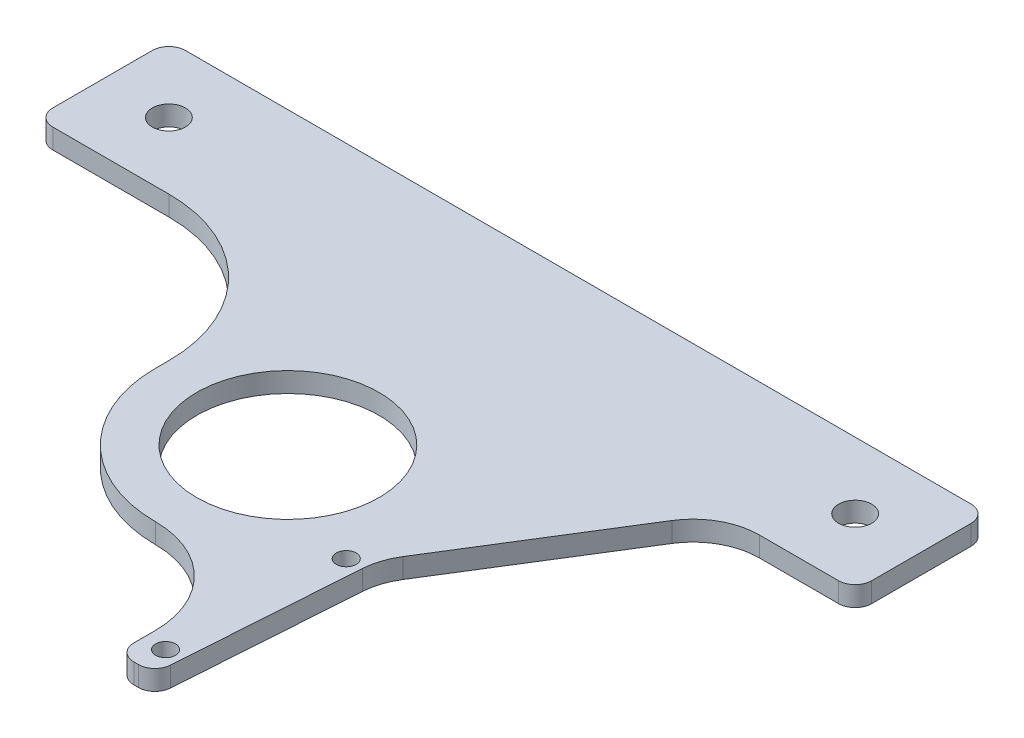
SolidWorks part; units mm, degrees
ref_plane "Front Plane" through (0, 0, 0) normal (0, 0, 1) x (1, 0, 0)
ref_plane "Top Plane" through (0, 0, 0) normal (0, 1, 0) x (1, 0, 0)
ref_plane "Right Plane" through (0, 0, 0) normal (1, 0, 0) x (0, 0, -1)
sketch "Sketch1" plane through (0, 0, 0) normal (0, 1, 0) x (1, 0, 0)
  line L10 (-123.5, 87.6) -> (123.5, 87.6)
  line L11 (-123.5, 172.6) -> (-123.5, 47.6) construction
  line L12 (123.5, 172.6) -> (123.5, 47.6) construction
  line L13 (123.5, 87.6) -> (123.5, 47.6)
  line L14 (-123.5, 87.6) -> (-123.5, 47.6)
  line L15 (35, -71.9) -> (38.5, -20.9) construction
  line L16 (39.7824, -75.2423) -> (43.5028, -21.0307)
  line L17 (123.5, 47.6) -> (94.6041, 47.6)
  line L18 (77.6286, 38.1751) -> (46.4804, -11.8249)
  line L19 (39.9883, -72.2423) -> (43.4883, -21.2423) construction
  line L21 (34.7941, -79.9) -> (33.4627, -79.9)
  line L23 (-83.5, 47.6) -> (-123.5, 47.6)
  line L24 (-40, 0) -> (-40, 4.1)
  line L25 (28.4627, -74.9) -> (28.4627, -68.4627)
  line L26 (-103.5, 47.6) -> (-103.5, 87.6) construction
  line L27 (0, -55) -> (0, 55) construction
  line L28 (103.5, 47.6) -> (103.5, 87.6) construction
  circle A0 centre (0, 0) radius 27.5
  circle A1 centre (38.5, -20.9) radius 3
  circle A2 centre (35, -71.9) radius 3
  arc A3 (-40, 0) -> (0, -40) centre (0, 0) ccw
  arc A4 (-40, 4.1) -> (-83.5, 47.6) centre (-83.5, 4.1) ccw
  arc A5 (0, -40) -> (28.4627, -68.4627) centre (0, -68.4627) cw
  arc A6 (94.6041, 47.6) -> (77.6286, 38.1751) centre (94.6041, 27.6) ccw
  arc A7 (43.5028, -21.0307) -> (46.4804, -11.8249) centre (63.4559, -22.4) cw
  arc A8 (33.4627, -79.9) -> (28.4627, -74.9) centre (33.4627, -74.9) cw
  arc A9 (34.7941, -79.9) -> (39.7824, -75.2423) centre (34.7941, -74.9) ccw
  circle A10 centre (-103.5, 67.6) radius 5
  circle A11 centre (103.5, 67.6) radius 5
  point P38 (83.5, 47.6)
  point P44 (28.4627, -79.9)
  point P47 (39.4627, -79.9)
  point P54 (-123.5, 67.6)
  dimension "D1" = 55
  dimension "D3" = 80
  dimension "D5" = 20
  dimension "D8" = 5
  dimension "D9" = 6
  dimension "D10" = 10
  dimension "D4" = 11
  dimension "D6" = 8
  dimension "D7" = 70
  dimension "D11" = 40
  dimension "D2" = 5
extrude "Boss-Extrude1" add sketch "Sketch1" along normal blind 6
fillet "Fillet1" radius 5 4 edges at (123.5, 3, -47.6) (123.5, 3, -87.6) (-123.5, 3, -87.6) (-123.5, 3, -47.6)
